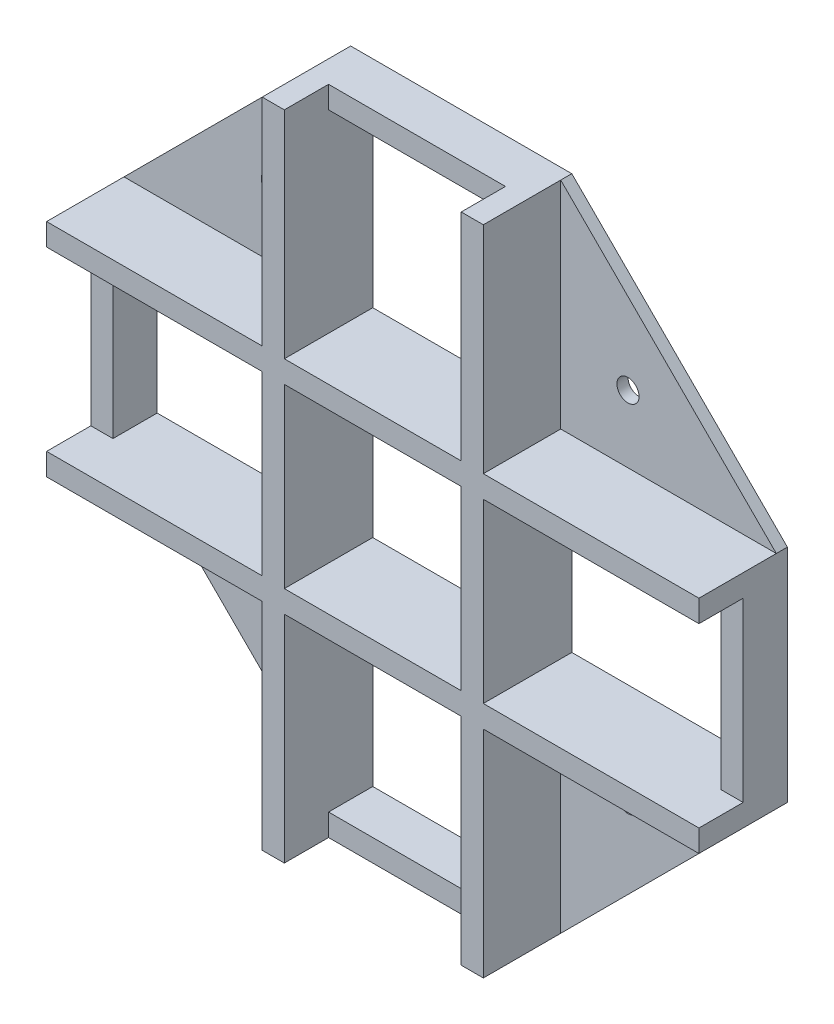
SolidWorks part; units mm, degrees
ref_plane "Front Plane" through (0, 0, 0) normal (0, 0, 1) x (1, 0, 0)
ref_plane "Top Plane" through (0, 0, 0) normal (0, 1, 0) x (1, 0, 0)
ref_plane "Right Plane" through (0, 0, 0) normal (1, 0, 0) x (0, 0, -1)
sketch "Sketch1" plane through (0, 0, 0) normal (0, 0, 1) x (1, 0, 0)
  line L1 (12.7, -37.465) -> (-12.7, -37.465)
  line L2 (12.7, -37.465) -> (12.7, 37.465)
  line L3 (12.7, 37.465) -> (-12.7, 37.465)
  line L4 (-12.7, -37.465) -> (-12.7, 37.465)
  line L5 (12.7, -37.465) -> (-12.7, 37.465) construction
  line L6 (12.7, 37.465) -> (-12.7, -37.465) construction
  line L7 (37.465, -12.7) -> (-37.465, -12.7)
  line L8 (37.465, -12.7) -> (37.465, 12.7)
  line L9 (37.465, 12.7) -> (-37.465, 12.7)
  line L10 (-37.465, -12.7) -> (-37.465, 12.7)
  line L11 (37.465, -12.7) -> (-37.465, 12.7) construction
  line L12 (37.465, 12.7) -> (-37.465, -12.7) construction
  point P0 (0, 0)
  point P6 (0, 0)
  dimension "D1" = 74.93
  dimension "D2" = 25.4
  dimension "D3" = 25.4
  dimension "D4" = 74.93
extrude "Boss-Extrude1" add sketch "Sketch1" along normal blind 10.16 contours L10 L7 L4 L9 | L2 L9 L4 L7 | L9 L2 L3 L4 | L8 L9 L2 L7 | L2 L7 L4 L1
sketch "Sketch2" plane through (0, 0, 10.16) normal (0, 0, 1) x (1, 0, 0)
  line L0 (0, 0) -> (0, 16.4382) construction
  line L1 (10.16, -10.16) -> (-10.16, -10.16)
  line L2 (10.16, -10.16) -> (10.16, 10.16)
  line L3 (10.16, 10.16) -> (-10.16, 10.16)
  line L4 (-10.16, -10.16) -> (-10.16, 10.16)
  line L5 (10.16, -10.16) -> (-10.16, 10.16) construction
  line L6 (10.16, 10.16) -> (-10.16, -10.16) construction
  line L7 (10.16, 12.7) -> (-10.16, 12.7)
  line L8 (10.16, 12.7) -> (10.16, 34.925)
  line L9 (10.16, 34.925) -> (-10.16, 34.925)
  line L10 (-10.16, 12.7) -> (-10.16, 34.925)
  line L11 (10.16, 12.7) -> (-10.16, 34.925) construction
  line L12 (10.16, 34.925) -> (-10.16, 12.7) construction
  line L13 (0, 0) -> (-32.0898, 0) construction
  line L14 (10.16, -34.925) -> (-10.16, -34.925)
  line L15 (-10.16, -12.7) -> (-10.16, -34.925)
  line L16 (10.16, -12.7) -> (-10.16, -12.7)
  line L17 (10.16, -12.7) -> (10.16, -34.925)
  line L18 (-34.925, 10.16) -> (-12.7, 10.16)
  line L19 (34.925, -10.16) -> (12.7, -10.16)
  line L20 (34.925, -10.16) -> (34.925, 10.16)
  line L21 (34.925, 10.16) -> (12.7, 10.16)
  line L22 (12.7, -10.16) -> (12.7, 10.16)
  line L23 (34.925, -10.16) -> (12.7, 10.16) construction
  line L24 (34.925, 10.16) -> (12.7, -10.16) construction
  line L25 (-12.7, -10.16) -> (-12.7, 10.16)
  line L26 (-34.925, -10.16) -> (-12.7, -10.16)
  line L27 (-34.925, -10.16) -> (-34.925, 10.16)
  point P0 (0, 0)
  point P6 (0, 23.8125)
  point P12 (0, 0)
  point P20 (23.8125, 0)
  dimension "D1" = 20.32
  dimension "D2" = 20.32
  dimension "D3" = 22.225
  dimension "D4" = 2.54
  dimension "D5" = 20.32
  dimension "D6" = 22.225
  dimension "D7" = 20.32
  dimension "D8" = 2.54
extrude "Cut-Extrude1" cut sketch "Sketch2" against normal blind 10.16
sketch "Sketch4" plane through (0, 0, 10.16) normal (0, 0, 1) x (1, 0, 0)
  line L0 (12.7, 37.465) -> (-12.7, 37.465) construction
  line L1 (10.16, 34.925) -> (-10.16, 34.925)
  line L2 (10.16, 34.925) -> (10.16, 37.465)
  line L3 (10.16, 37.465) -> (-10.16, 37.465)
  line L4 (-10.16, 34.925) -> (-10.16, 37.465)
  line L5 (10.16, 12.7) -> (10.16, 34.925) construction
  line L6 (-10.16, 34.925) -> (-10.16, 12.7) construction
  line L12 (37.465, -12.7) -> (37.465, 12.7) construction
  line L13 (34.925, 10.16) -> (37.465, 10.16)
  line L14 (34.925, 10.16) -> (34.925, -10.16)
  line L15 (34.925, -10.16) -> (37.465, -10.16)
  line L16 (37.465, 10.16) -> (37.465, -10.16)
  line L17 (12.7, -10.16) -> (34.925, -10.16) construction
  line L18 (34.925, 10.16) -> (12.7, 10.16) construction
  line L19 (0, 0) -> (17.8539, 0) construction
  line L20 (0, 0) -> (0, -24.0674) construction
  line L21 (-34.925, -10.16) -> (-37.465, -10.16)
  line L22 (-34.925, 10.16) -> (-37.465, 10.16)
  line L23 (-34.925, 10.16) -> (-34.925, -10.16)
  line L24 (-37.465, 10.16) -> (-37.465, -10.16)
  line L25 (10.16, -37.465) -> (-10.16, -37.465)
  line L26 (-10.16, -34.925) -> (-10.16, -37.465)
  line L27 (10.16, -34.925) -> (-10.16, -34.925)
  line L28 (10.16, -34.925) -> (10.16, -37.465)
extrude "Cut-Extrude2" cut sketch "Sketch4" against normal blind 5.08
sketch "Sketch5" plane through (0, 0, 0) normal (0, 0, 1) x (1, 0, 0)
  line L0 (-37.465, 12.7) -> (-12.7, 37.465)
  line L1 (-12.7, 37.465) -> (-12.7, 12.7)
  line L2 (-12.7, 12.7) -> (-37.465, 12.7)
  line L3 (12.7, 37.465) -> (37.465, 12.7)
  line L4 (37.465, 12.7) -> (12.7, 12.7)
  line L5 (12.7, 12.7) -> (12.7, 37.465)
  line L6 (0, 0) -> (7.2753, 7.2753) construction
  line L7 (0, 0) -> (-12.7, 12.7) construction
  line L8 (37.465, -12.7) -> (12.7, -12.7)
  line L9 (12.7, -37.465) -> (37.465, -12.7)
  line L10 (12.7, -12.7) -> (12.7, -37.465)
  line L11 (-12.7, -37.465) -> (-12.7, -12.7)
  line L12 (-37.465, -12.7) -> (-12.7, -37.465)
  line L13 (-12.7, -12.7) -> (-37.465, -12.7)
extrude "Boss-Extrude2" add sketch "Sketch5" along normal blind 1.27
sketch "Sketch6" plane through (0, 0, 1.27) normal (0, 0, 1) x (1, 0, 0)
  line L0 (0, 0) -> (-10.16, 10.16) construction
  line L1 (0, 0) -> (10.16, 10.16) construction
  circle A0 centre (-20.4251, 20.4251) radius 1.27
  circle A1 centre (20.4251, 20.4251) radius 1.27
  circle A2 centre (20.4251, -20.4251) radius 1.27
  circle A3 centre (-20.4251, -20.4251) radius 1.27
  dimension "D1" = 10.925
  dimension "D2" = 2.54
  dimension "D4" = 2.54
  dimension "D3" = 10.925
extrude "Cut-Extrude3" cut sketch "Sketch6" against normal blind 1.27
